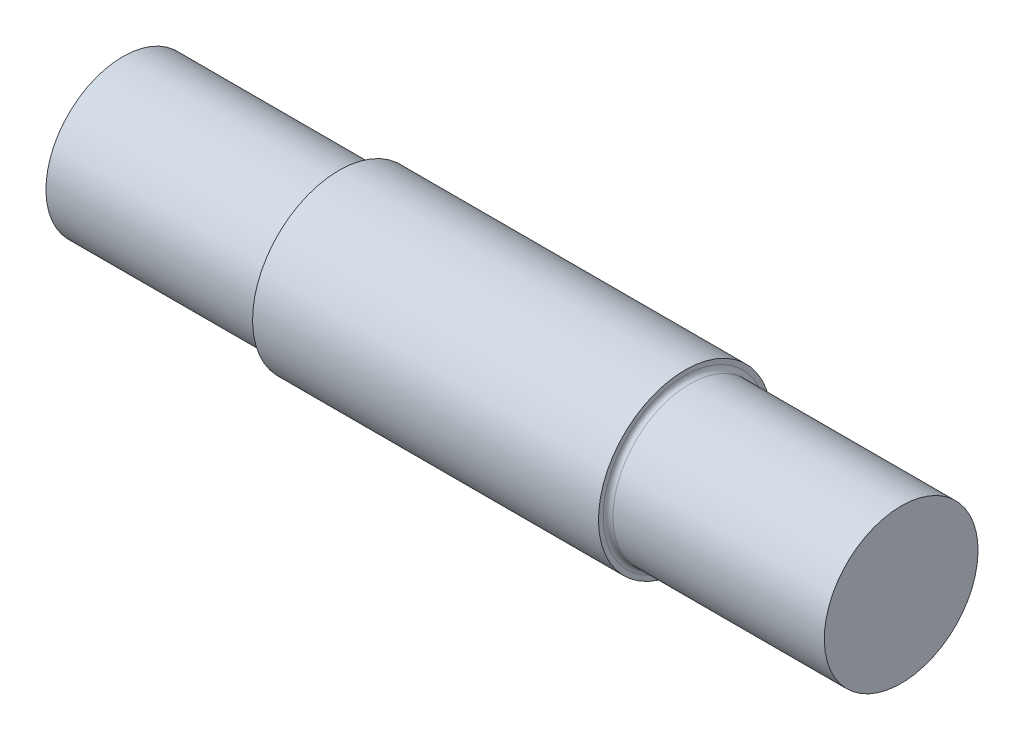
SolidWorks part; units mm, degrees
ref_plane "Ön Düzlem" through (0, 0, 0) normal (0, 0, 1) x (1, 0, 0)
ref_plane "Üst Düzlem" through (0, 0, 0) normal (0, 1, 0) x (1, 0, 0)
ref_plane "Sağ Düzlem" through (0, 0, 0) normal (1, 0, 0) x (0, 0, -1)
sketch "Çizim1" plane through (0, 0, 0) normal (0, 0, 1) x (1, 0, 0)
  line L0 (0, 0) -> (0, 8)
  line L1 (0, 8) -> (22.5, 8)
  line L2 (22.5, 8) -> (22.5, 9)
  line L3 (22.5, 9) -> (58.5, 9)
  line L4 (58.5, 9) -> (58.5, 8)
  line L5 (58.5, 8) -> (81, 8)
  line L6 (81, 8) -> (81, 0)
  line L7 (81, 0) -> (0, 0)
  dimension "D1" = 81
  dimension "D2" = 36
  dimension "D3" = 9
  dimension "D4" = 8
revolve "Döndür2" add sketch "Çizim1" angle 360 about L7
cosmetic thread "Kozmetik Diş Açma1" parameters "D1"=5, "D2"=14.344
cosmetic thread "Kozmetik Diş Açma2" parameters "D1"=5, "D2"=14.344
fillet "Radyus2" radius 0.5 2 edges at (22.5, 8, 0) (58.5, 8, 0)
